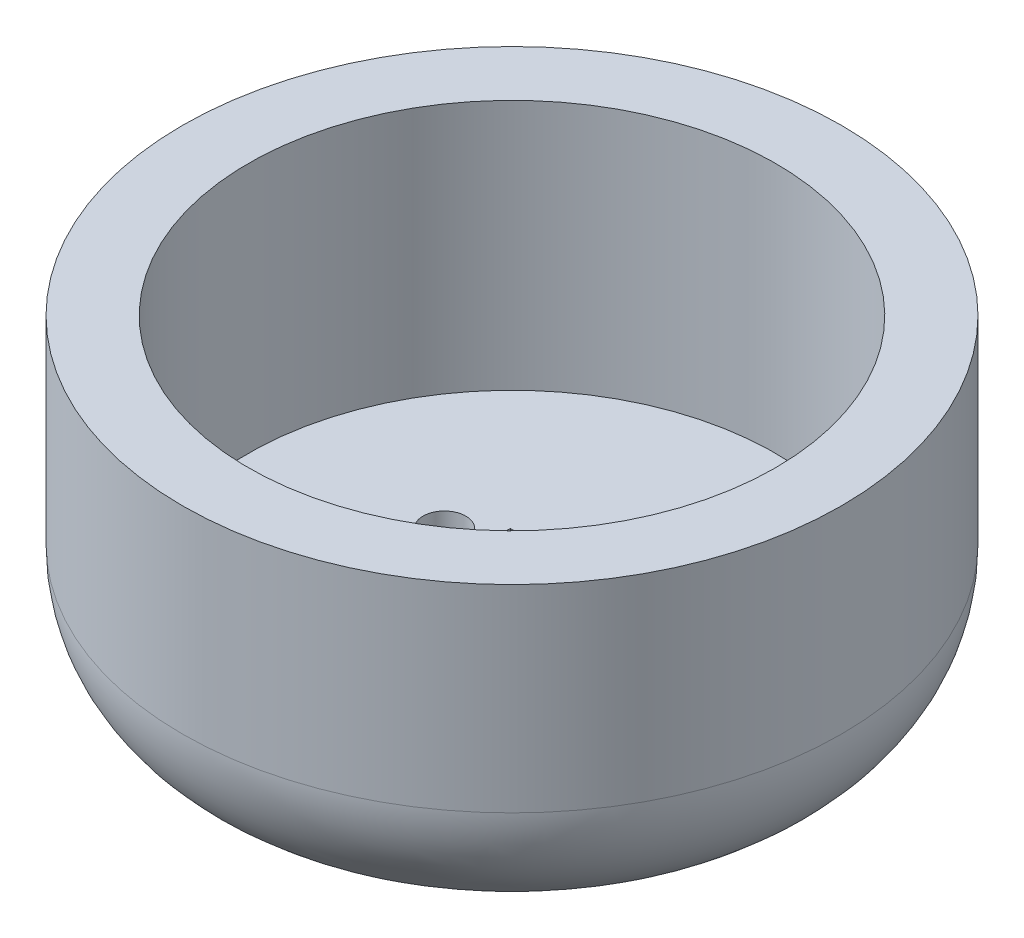
SolidWorks part; units mm, degrees
ref_plane "Front Plane" through (0, 0, 0) normal (0, 0, 1) x (1, 0, 0)
ref_plane "Top Plane" through (0, 0, 0) normal (0, 1, 0) x (1, 0, 0)
ref_plane "Right Plane" through (0, 0, 0) normal (1, 0, 0) x (0, 0, -1)
sketch "Sketch5" plane through (0, 0, 0) normal (0, 0, 1) x (1, 0, 0)
  line L0 (0, 0) -> (-50, 0)
  line L1 (-50, 0) -> (-50, 50)
  line L2 (-50, 50) -> (-40, 50)
  line L3 (-40, 50) -> (-40, 11.9)
  line L4 (-40, 11.9) -> (0, 11.9)
  line L5 (0, 11.9) -> (0, 0)
  line L6 (0, 0) -> (0, 37.3397) construction
  dimension "D1" = 11.9
  dimension "D2" = 50
  dimension "D3" = 50
  dimension "D4" = 10
revolve "Revolve1" add sketch "Sketch5" angle 360 about L6
fillet "Fillet1" radius 20 1 edges at (50, 0, 0)
sketch "Sketch6" plane through (0, 11.9, 0) normal (0, 1, 0) x (1, 0, 0)
  line L0 (0, 0) -> (-20.5, 0) construction
  line L1 (-10.25, -10) -> (29.25, -10)
  line L2 (-10.25, -10) -> (-10.25, 10)
  line L3 (-10.25, 10) -> (29.25, 10)
  line L4 (29.25, -10) -> (29.25, 10)
  circle A0 centre (0, 0) radius 6.375
  point P7 (-10.25, 0)
  dimension "D1" = 12.75
  dimension "D2" = 20
  dimension "D3" = 39.5
  dimension "D4" = 10.25
  dimension "D5" = 180
extrude "Cut-Extrude1" cut sketch "Sketch6" against normal blind 9.9
sketch "Sketch8" plane through (0, 11.9, 0) normal (0, 1, 0) x (1, 0, 0)
  circle A0 centre (0, 0) radius 6.375
extrude "Cut-Extrude2" cut sketch "Sketch8" against normal blind 37.9
sketch "Sketch9" plane through (0, 11.9, 0) normal (0, 1, 0) x (1, 0, 0)
  line L0 (-10.25, 0) -> (29.25, 0) construction
  line L1 (-10.25, -10) -> (-10.25, 10) construction
  line L2 (29.25, -10) -> (29.25, 10) construction
  line L3 (9.5, 10) -> (9.5, -10) construction
  line L4 (-10.25, 10) -> (29.25, 10) construction
  line L5 (-10.25, -10) -> (29.25, -10) construction
  line L6 (-10.25, -10) -> (-10.25, 10) construction
  line L7 (-10.25, 10) -> (29.25, 10) construction
  circle A0 centre (-15.25, 5) radius 3.25
  circle A1 centre (34.25, 5) radius 3.25
  circle A2 centre (34.25, -5) radius 3.25
  circle A3 centre (-15.25, -5) radius 3.25
  dimension "D1" = 6.5
  dimension "D2" = 5
  dimension "D3" = 5
extrude "Cut-Extrude3" cut sketch "Sketch9" against normal blind 37.9
